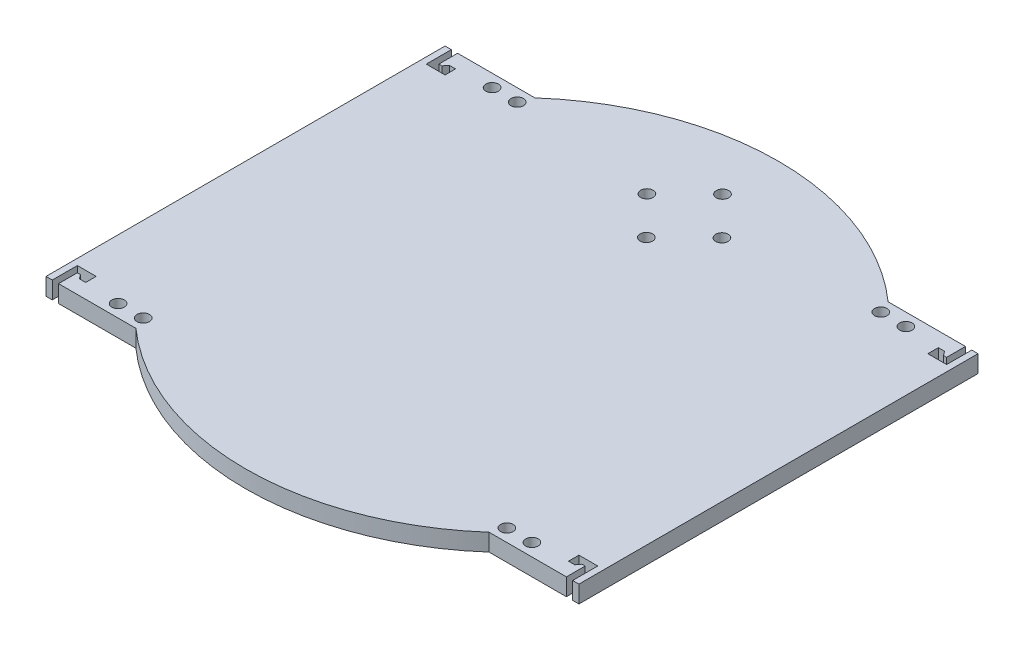
SolidWorks part; units mm, degrees
ref_plane "Front Plane" through (0, 0, 0) normal (0, 0, 1) x (1, 0, 0)
ref_plane "Top Plane" through (0, 0, 0) normal (0, 1, 0) x (1, 0, 0)
ref_plane "Right Plane" through (0, 0, 0) normal (1, 0, 0) x (0, 0, -1)
sketch "Sketch4" plane through (0, 0, 0) normal (0, 1, 0) x (1, 0, 0)
  line L25 (56.3354, 63.65) -> (81, 63.65)
  line L26 (-85, -63.65) -> (-83, -63.65)
  line L31 (-85, -63.65) -> (-85, 63.65)
  line L32 (-85, 63.65) -> (-83, 63.65)
  line L34 (85, -63.65) -> (85, 63.65)
  line L35 (-85, -63.65) -> (85, 63.65) construction
  line L36 (-85, 63.65) -> (85, -63.65) construction
  line L37 (0, 0) -> (0, 85) construction
  line L38 (56.3354, -63.65) -> (81, -63.65)
  line L39 (0, 0) -> (-85, 0) construction
  line L40 (-83, 55.65) -> (-77, 55.65)
  line L41 (-77, 55.65) -> (-77, 58.9927)
  line L43 (-83, 63.65) -> (-83, 55.65)
  line L45 (-81, 63.65) -> (-81, 57.6594)
  line L48 (-81, 57.6594) -> (-80, 57.6594)
  line L50 (-79, 58.9927) -> (-80, 57.6594)
  line L51 (-79, 58.9927) -> (-77, 58.9927)
  line L52 (-81, 63.65) -> (-56.3354, 63.65)
  line L53 (81, 63.65) -> (81, 57.6594)
  line L54 (81, 57.6594) -> (80, 57.6594)
  line L55 (79, 58.9927) -> (80, 57.6594)
  line L56 (79, 58.9927) -> (77, 58.9927)
  line L57 (77, 55.65) -> (77, 58.9927)
  line L58 (83, 55.65) -> (77, 55.65)
  line L59 (83, 63.65) -> (83, 55.65)
  line L60 (-81, -63.65) -> (-81, -57.6594)
  line L61 (-81, -57.6594) -> (-80, -57.6594)
  line L62 (-79, -58.9927) -> (-80, -57.6594)
  line L63 (-79, -58.9927) -> (-77, -58.9927)
  line L64 (-77, -55.65) -> (-77, -58.9927)
  line L65 (-83, -55.65) -> (-77, -55.65)
  line L66 (-83, -63.65) -> (-83, -55.65)
  line L67 (83, -63.65) -> (83, -55.65)
  line L68 (81, -63.65) -> (81, -57.6594)
  line L69 (81, -57.6594) -> (80, -57.6594)
  line L70 (79, -58.9927) -> (80, -57.6594)
  line L71 (79, -58.9927) -> (77, -58.9927)
  line L72 (77, -55.65) -> (77, -58.9927)
  line L73 (83, -55.65) -> (77, -55.65)
  line L74 (83, 63.65) -> (85, 63.65)
  line L75 (83, -63.65) -> (85, -63.65)
  line L76 (-81, -63.65) -> (-56.3354, -63.65)
  arc A36 (-56.3354, -63.65) -> (56.3354, -63.65) centre (0, 0) ccw
  circle A37 centre (0, 0) radius 75 construction
  arc A38 (56.3354, 63.65) -> (-56.3354, 63.65) centre (0, 0) ccw
  circle A47 centre (-58, 59.65) radius 2
  circle A48 centre (-66, 59.65) radius 2
  circle A49 centre (66, 59.65) radius 2
  circle A50 centre (58, 59.65) radius 2
  circle A51 centre (66, -59.65) radius 2
  circle A52 centre (58, -59.65) radius 2
  circle A53 centre (-58, -59.65) radius 2
  circle A54 centre (-66, -59.65) radius 2
  circle A55 centre (12.1486, 54.8125) radius 2
  circle A56 centre (0, 42.85) radius 2
  circle A57 centre (-11.9625, 54.9986) radius 2
  circle A58 centre (0.1861, 66.961) radius 2
  point P30 (-58, 59.65)
  point P61 (0, 55)
  point P62 (12.1486, 54.8125)
  point P74 (0.093, 54.9055)
  dimension "D1" = 150
  dimension "D3" = 24.6646
  dimension "D6" = 66
  dimension "D8" = 2
  dimension "D11" = 1.3333
  dimension "D14" = 4
  dimension "D4" = 170
  dimension "D13" = 2
  dimension "D10" = 1
  dimension "D2" = 170
  dimension "D5" = 4
  dimension "D12" = 4
  dimension "D7" = 2
  dimension "D9" = 6
  dimension "D15" = 2.0094
  dimension "D16" = 4
  dimension "D17" = 4
  dimension "D18" = 8
  dimension "D19" = 8
  dimension "D20" = 11.9625
  dimension "D21" = 12.1486
extrude "Boss-Extrude1" add sketch "Sketch4" along normal blind 5.5
